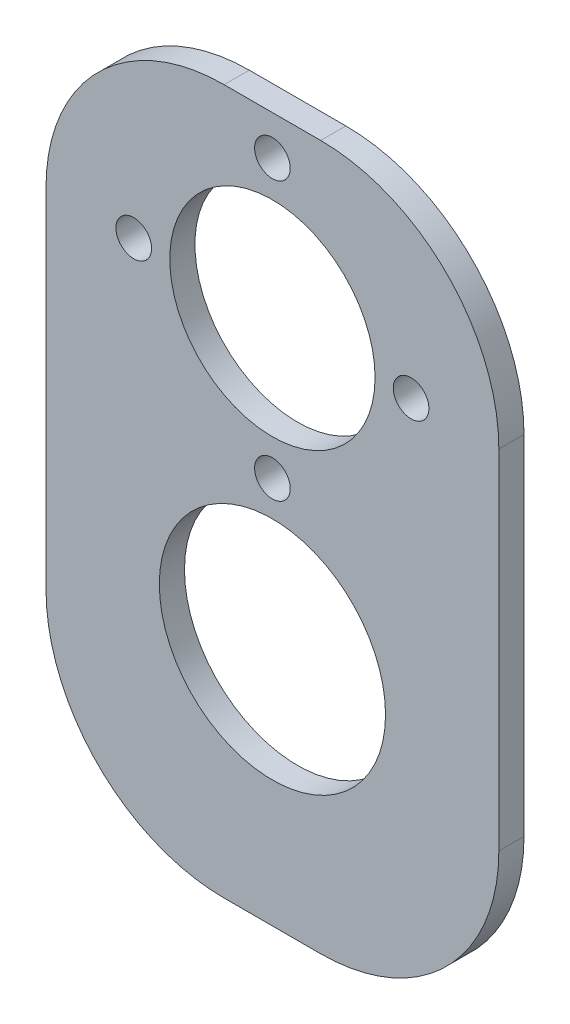
SolidWorks part; units mm, degrees
ref_plane "Front Plane" through (0, 0, 0) normal (0, 0, 1) x (1, 0, 0)
ref_plane "Top Plane" through (0, 0, 0) normal (0, 1, 0) x (1, 0, 0)
ref_plane "Right Plane" through (0, 0, 0) normal (1, 0, 0) x (0, 0, -1)
sketch "Sketch1" plane through (0, 0, 0) normal (0, 0, 1) x (1, 0, 0)
  line L0 (28.575, -34.4358) -> (-28.575, -34.4358)
  line L1 (-28.575, 54.4642) -> (28.575, 54.4642)
  line L2 (-28.575, 54.4642) -> (-28.575, -34.4358)
  line L3 (-28.575, -34.4358) -> (-28.3009, -34.7981)
  line L4 (28.575, 54.4642) -> (28.575, -34.4358)
  circle A0 centre (0, 31.9852) radius 12.954
  circle A1 centre (0, 49.4858) radius 2.25
  circle A2 centre (17.5006, 31.9852) radius 2.25
  circle A3 centre (0, 14.4846) radius 2.25
  circle A4 centre (-17.5006, 31.9852) radius 2.25
  circle A5 centre (0, -4.2098) radius 14.2748
  point P20 (0, 31.9852)
  dimension "D5" = 28.575
  dimension "D6" = 28.575
  dimension "D13" = 22.479
  dimension "D3" = 88.9
  dimension "D9" = 11.0744
  dimension "D10" = 4.9784
  dimension "D18" = 4.5
  dimension "D19" = 25.908
  dimension "D15" = 4.5
  dimension "D16" = 4.5
  dimension "D17" = 4.5
  dimension "D22" = 28.5496
  dimension "D2" = 57.15
  dimension "D7" = 28.575
  dimension "D8" = 46.0756
  dimension "D11" = 22.479
  dimension "D12" = 22.479
  dimension "D14" = 39.9796
  dimension "D20" = 28.575
  dimension "D21" = 58.674
extrude "Boss-Extrude1" add sketch "Sketch1" along normal blind 3.175 contours L4 L1 L2 L0 A5 A4 A3 A2 A1 A0
fillet "Fillet1" radius 22.479 4 edges at (28.575, -34.4358, 1.5875) (-28.575, -34.4358, 1.5875) (28.575, 54.4642, 1.5875) (-28.575, 54.4642, 1.5875)
